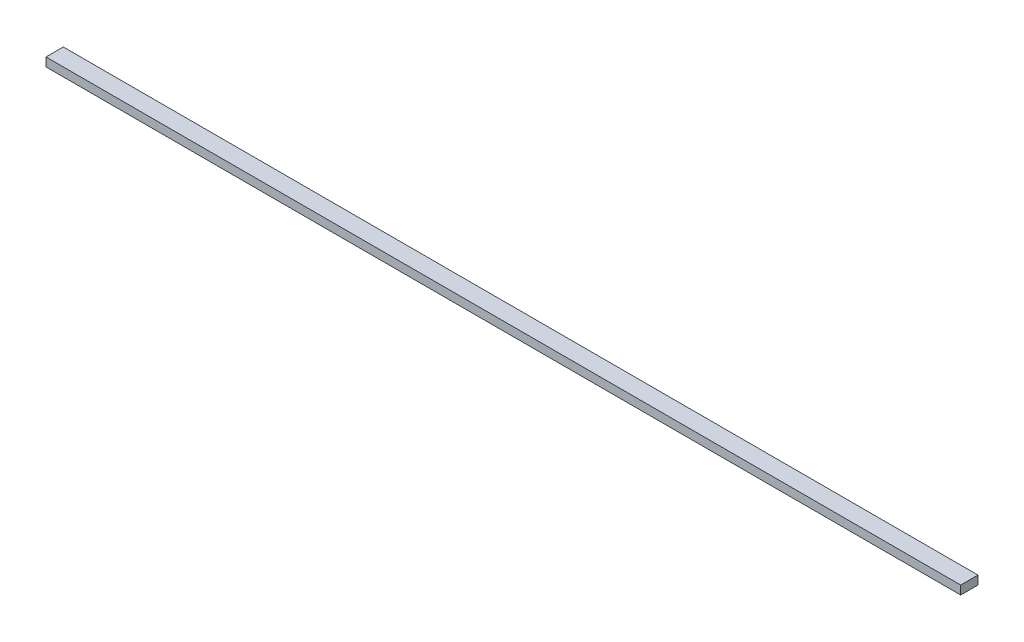
SolidWorks part; units mm, degrees
ref_plane "Front Plane" through (0, 0, 0) normal (0, 0, 1) x (1, 0, 0)
ref_plane "Top Plane" through (0, 0, 0) normal (0, 1, 0) x (1, 0, 0)
ref_plane "Right Plane" through (0, 0, 0) normal (1, 0, 0) x (0, 0, -1)
sketch "Sketch1" plane through (0, 0, 0) normal (0, 0, 1) x (1, 0, 0)
  line L1 (335.7562, 3.175) -> (-335.7563, 3.175)
  line L2 (335.7562, 3.175) -> (335.7562, -3.175)
  line L3 (335.7562, -3.175) -> (-335.7563, -3.175)
  line L4 (-335.7563, 3.175) -> (-335.7563, -3.175)
  line L5 (335.7562, 3.175) -> (-335.7563, -3.175) construction
  line L6 (335.7562, -3.175) -> (-335.7563, 3.175) construction
  point P0 (0, 0)
  dimension "D1" = 6.35
  dimension "D2" = 671.5125
extrude "Boss-Extrude1" add sketch "Sketch1" along normal blind 12.7
